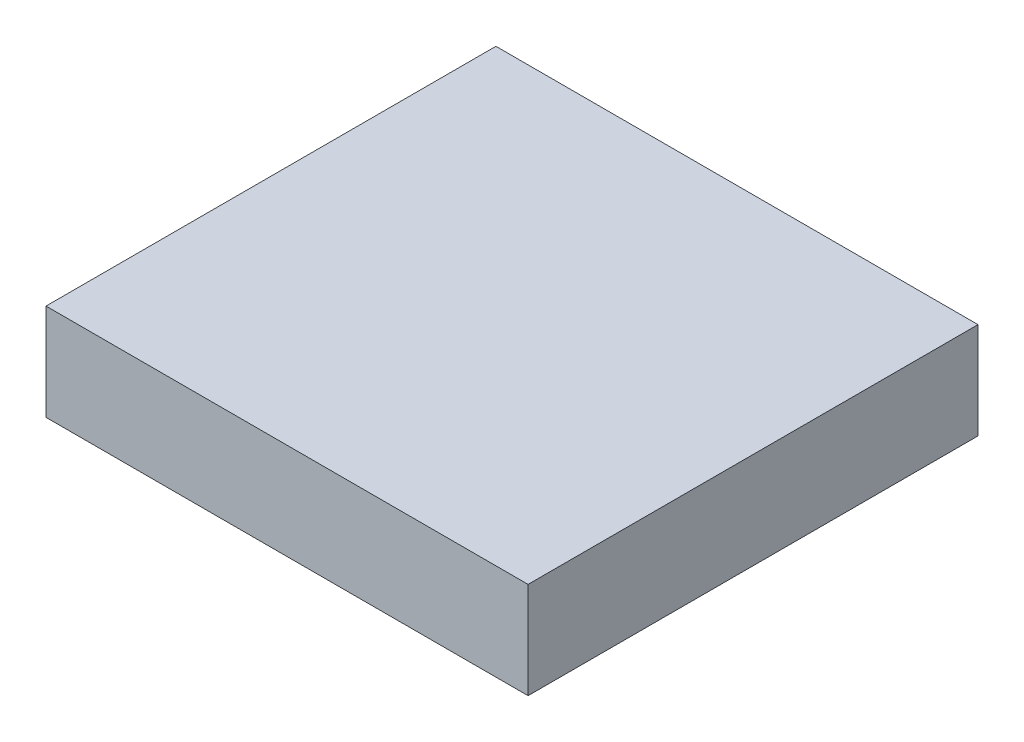
SolidWorks part; units mm, degrees
ref_plane "Plano frontal" through (0, 0, 0) normal (0, 0, 1) x (1, 0, 0)
ref_plane "Plano superior" through (0, 0, 0) normal (0, 1, 0) x (1, 0, 0)
ref_plane "Plano direito" through (0, 0, 0) normal (1, 0, 0) x (0, 0, -1)
sketch "Esboço1" plane through (0, 0, 0) normal (0, 1, 0) x (1, 0, 0)
  line L1 (-75, -70) -> (75, -70)
  line L2 (-75, -70) -> (-75, 70)
  line L3 (-75, 70) -> (75, 70)
  line L4 (75, -70) -> (75, 70)
  line L5 (-75, -70) -> (75, 70) construction
  line L6 (-75, 70) -> (75, -70) construction
  point P0 (0, 0)
  dimension "D1" = 140
  dimension "D2" = 150
extrude "Ressalto-extrusão1" add sketch "Esboço1" along normal mid plane 30
move or copy body "Corpo-Converter em corpo de malha1" [suppressed] bodies to move or copy 101 copy no translate (0, 0, 0) parameters "D1"=0, "D2"=0, "D3"=0
